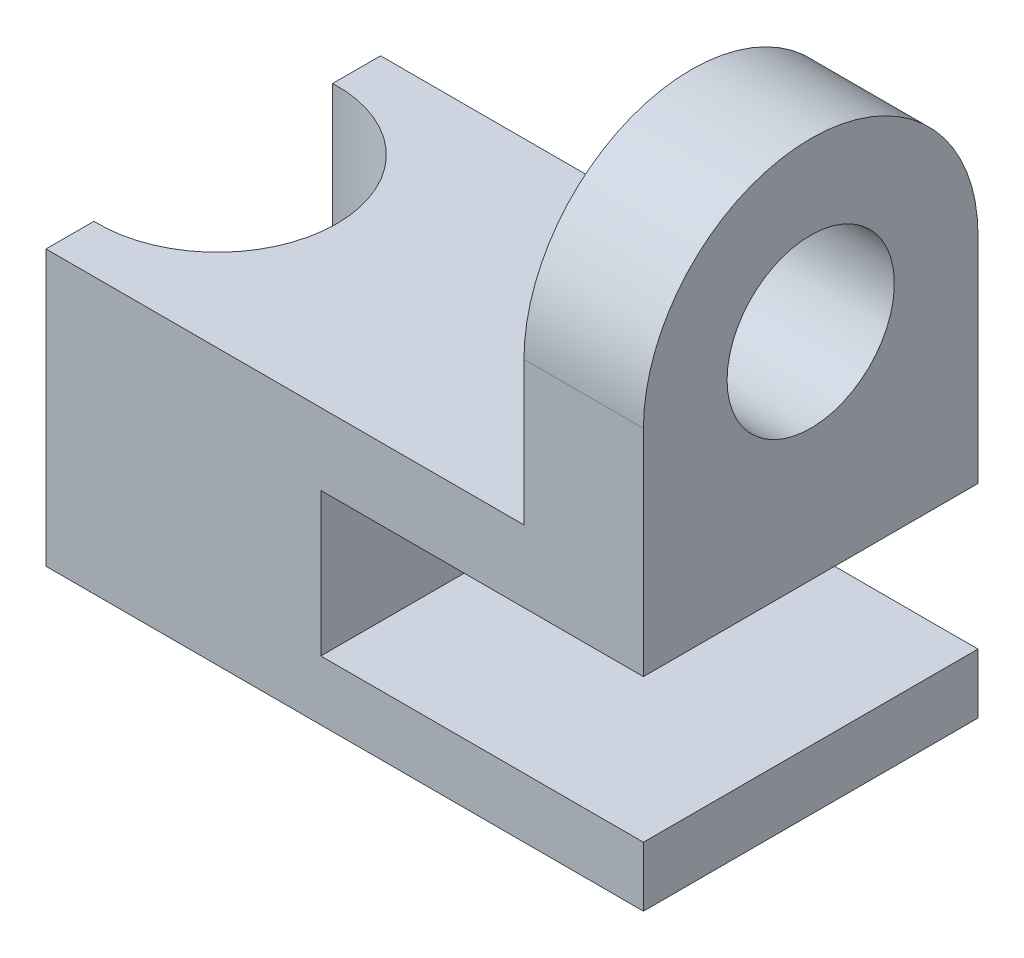
SolidWorks part; units mm, degrees
ref_plane "Front Plane" through (0, 0, 0) normal (0, 0, 1) x (1, 0, 0)
ref_plane "Top Plane" through (0, 0, 0) normal (0, 1, 0) x (1, 0, 0)
ref_plane "Right Plane" through (0, 0, 0) normal (1, 0, 0) x (0, 0, -1)
sketch "Sketch1" plane through (0, 0, 0) normal (0, 0, 1) x (1, 0, 0)
  line L0 (0, 0) -> (0, -5000)
  line L1 (0, -5000) -> (-50000, -5000)
  line L2 (-50000, -5000) -> (-50000, 18000)
  line L3 (-50000, 18000) -> (-10000, 18000)
  line L4 (-10000, 18000) -> (-10000, 30000)
  line L5 (-10000, 30000) -> (0, 30000)
  line L6 (0, 30000) -> (0, 12000)
  line L7 (0, 12000) -> (-27000, 12000)
  line L8 (-27000, 12000) -> (-27000, 0)
  line L9 (-27000, 0) -> (0, 0)
  dimension "D1" = 50000
  dimension "D2" = 27000
  dimension "D3" = 6000
  dimension "D4" = 12000
  dimension "D5" = 5000
  dimension "D6" = 40000
  dimension "D7" = 10000
  dimension "D8" = 18000
extrude "Boss-Extrude1" add sketch "Sketch1" along normal blind 28000
sketch "Sketch2" plane through (0, 18000, 0) normal (0, 1, 0) x (1, 0, 0)
  line L0 (-55725.9021, -14000) -> (-27508.928, -14000) construction
  line L4 (-50000, -28000) -> (-50000, 0) construction
  line L5 (-50000, -4005.7946) -> (-50000, -23994.2054)
  arc A0 (-50000, -23994.2054) -> (-50000, -4005.7946) centre (-49659.6193, -14000) ccw
  dimension "D1" = 10000
  dimension "D2" = 14000
extrude "Cut-Extrude1" cut sketch "Sketch2" against normal through all
sketch "Sketch3" plane through (-10000, 0, 0) normal (-1, 0, 0) x (0, 0, 1)
  line L0 (28000, 30000) -> (0, 30000) construction
  line L1 (14000, 51815.9492) -> (14000, 12594.8809) construction
  line L2 (-10998.9864, 30000) -> (40932.6132, 30000) construction
  arc A0 (28000, 30000) -> (0, 30000) centre (14000, 30000) ccw
  arc A1 (21000, 30000) -> (7000, 30000) centre (14000, 30000) ccw
  line M6 (28000, 30000) -> (0, 30000)
  dimension "D1" = 14000
extrude "Boss-Extrude2" add sketch "Sketch3" against normal through all contours A1 A0 M6
sketch "Sketch4" plane through (-10000, 0, 0) normal (-1, 0, 0) x (0, 0, 1)
  line L0 (21000, 30000) -> (7000, 30000) construction
  line L1 (7000, 30000) -> (21000, 30000)
  arc A0 (21000, 30000) -> (7000, 30000) centre (14000, 30000) cw
extrude "Cut-Extrude2" cut sketch "Sketch4" against normal through all
